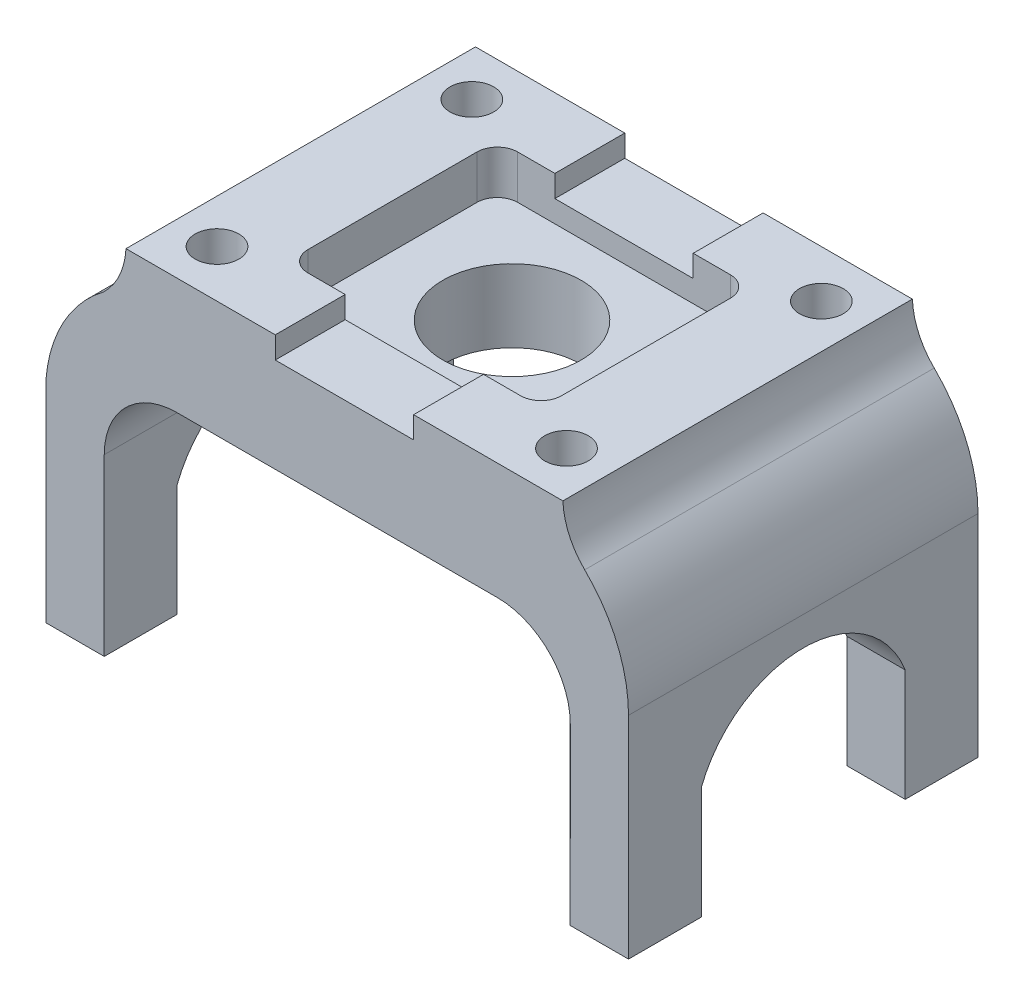
SolidWorks part; units mm, degrees
ref_plane "Front Plane" through (0, 0, 0) normal (0, 0, 1) x (1, 0, 0)
ref_plane "Top Plane" through (0, 0, 0) normal (0, 1, 0) x (1, 0, 0)
ref_plane "Right Plane" through (0, 0, 0) normal (1, 0, 0) x (0, 0, -1)
sketch "Sketch3" plane through (0, 0, 0) normal (0, 0, 1) x (1, 0, 0)
  line L0 (-27.94, 0.0309) -> (27.94, 0.0309)
  line L1 (40.64, -12.6691) -> (40.64, -43.1491)
  line L2 (40.64, -43.1491) -> (50.8, -43.1491)
  line L3 (50.8, -43.1491) -> (50.8, -6.3191)
  line L4 (39.3533, 20.3509) -> (13.3183, 20.3509)
  line L5 (13.3183, 20.3509) -> (13.3183, 16.5409)
  line L6 (13.3183, 16.5409) -> (-10.8117, 16.5409)
  line L8 (-10.8117, 20.3509) -> (-10.8117, 16.5409)
  line L9 (-36.8467, 20.3509) -> (-10.8117, 20.3509)
  line L10 (-50.8, -43.1491) -> (-50.8, -6.3191)
  line L11 (-40.64, -43.1491) -> (-50.8, -43.1491)
  line L12 (-40.64, -12.6691) -> (-40.64, -43.1491)
  arc A1 (50.8, -6.3191) -> (43.1604, 11.8393) centre (25.4, -6.3191) ccw
  arc A2 (43.1604, 11.8393) -> (39.3533, 20.3509) centre (52.0406, 20.9185) cw
  arc A3 (40.64, -12.6691) -> (27.94, 0.0309) centre (27.94, -12.6691) ccw
  arc A4 (-40.7808, 11.8393) -> (-36.8467, 20.3509) centre (-49.5276, 21.0471) ccw
  arc A5 (-50.8, -6.3191) -> (-40.7808, 11.8393) centre (-25.4888, -8.4416) cw
  arc A6 (-40.64, -12.6691) -> (-27.94, 0.0309) centre (-27.94, -12.6691) cw
  dimension "D4" = 30.48
  dimension "D7" = 25.4
  dimension "D8" = 12.7
  dimension "D9" = 12.7
  dimension "D14" = 25.4
  dimension "D15" = 12.7
  dimension "D1" = 3.81
  dimension "D2" = 76.2
  dimension "D3" = 24.13
  dimension "D5" = 101.6
  dimension "D6" = 30.48
  dimension "D10" = 36.83
  dimension "D11" = 20.32
  dimension "D12" = 81.28
extrude "Boss-Extrude1" add sketch "Sketch3" against normal blind 60.96
sketch "Sketch4" plane through (50.8, 0, 0) normal (1, 0, 0) x (0, 0, -1)
  line L0 (12.7, -43.1491) -> (12.7, -23.5911)
  line L1 (60.96, -43.1491) -> (0, -43.1491) construction
  line L2 (48.26, -43.1491) -> (48.26, -23.5911)
  line L3 (12.7, -43.1491) -> (48.26, -43.1491)
  line L4 (0, -43.1491) -> (0, -6.3191) construction
  arc A0 (12.7, -23.5911) -> (48.26, -23.5911) centre (30.48, -30.4303) cw
  dimension "D1" = 19.05
  dimension "D2" = 19.558
  dimension "D3" = 19.558
  dimension "D4" = 12.7
  dimension "D5" = 17.78
extrude "Cut-Extrude1" cut sketch "Sketch4" against normal blind 101.6
ref_plane "Plane1" through (0, 20.3509, 0) normal (0, 1, 0) x (1, 0, 0)
sketch "Sketch5" plane through (0, 20.3509, 0) normal (0, 1, 0) x (1, 0, 0)
  line L5 (-20.8447, 45.212) -> (-20.8447, 15.748)
  line L6 (-17.2887, 12.192) -> (19.7953, 12.192)
  line L17 (23.3513, 15.748) -> (23.3513, 45.212)
  line L18 (19.7953, 48.768) -> (-17.2887, 48.768)
  line L19 (13.3183, 60.96) -> (-10.8117, 60.96) construction
  line L20 (39.3533, 0) -> (13.3183, 0) construction
  line L21 (39.3533, 60.96) -> (39.3533, 0) construction
  line L22 (-36.8467, 60.96) -> (-36.8467, 0) construction
  arc A4 (19.7953, 12.192) -> (23.3513, 15.748) centre (19.7953, 15.748) ccw
  arc A5 (-20.8447, 15.748) -> (-17.2887, 12.192) centre (-17.2887, 15.748) ccw
  arc A6 (23.3513, 45.212) -> (19.7953, 48.768) centre (19.7953, 45.212) ccw
  arc A7 (-20.8447, 45.212) -> (-17.2887, 48.768) centre (-17.2887, 45.212) cw
  point P0 (0, 30.48)
  dimension "D5" = 3.556
  dimension "D1" = 12.192
  dimension "D2" = 12.192
  dimension "D3" = 16.002
  dimension "D4" = 16.002
extrude "Cut-Extrude2" cut sketch "Sketch5" against normal blind 7.62
sketch "Sketch6" plane through (0, 12.7309, 0) normal (0, 1, 0) x (1, 0, 0)
  circle A0 centre (0, 30.48) radius 12.065
  dimension "D1" = 24.13
extrude "Cut-Extrude3" cut sketch "Sketch6" against normal blind 12.7
sketch "Sketch7" plane through (0, 20.3509, 0) normal (0, 1, 0) x (1, 0, 0)
  line L0 (-10.8117, 60.96) -> (-36.8467, 60.96) construction
  line L1 (-36.8467, 60.96) -> (-36.8467, 0) construction
  circle A0 centre (-29.2267, 52.705) radius 3.81
  circle A1 centre (31.7333, 52.705) radius 3.81
  circle A2 centre (31.7333, 8.255) radius 3.81
  circle A3 centre (-29.2267, 8.255) radius 3.81
  dimension "D3" = 7.62
  dimension "D1" = 8.255
  dimension "D2" = 7.62
  dimension "D4" = 2
  dimension "D5" = 2
extrude "Cut-Extrude5" cut sketch "Sketch7" against normal through all
